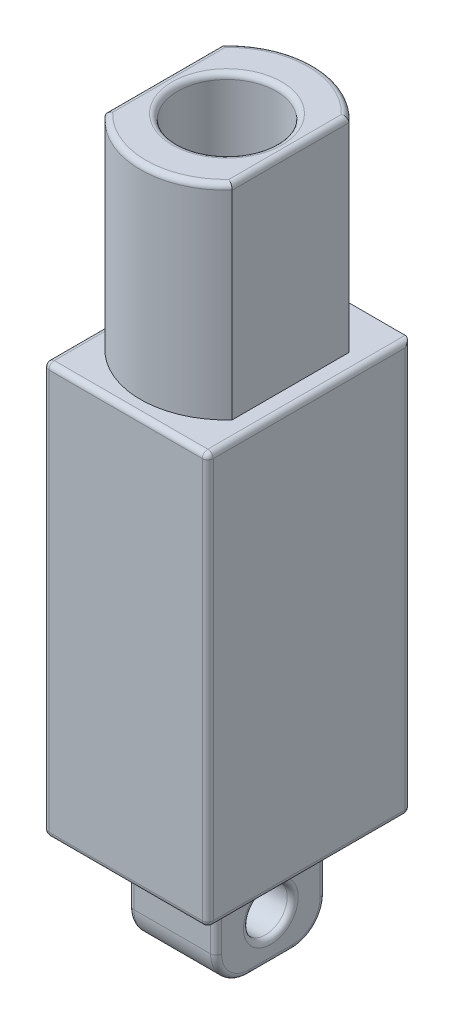
SolidWorks part; units mm, degrees
ref_plane "Front Plane" through (0, 0, 0) normal (0, 0, 1) x (1, 0, 0)
ref_plane "Top Plane" through (0, 0, 0) normal (0, 1, 0) x (1, 0, 0)
ref_plane "Right Plane" through (0, 0, 0) normal (1, 0, 0) x (0, 0, -1)
sketch "Sketch1" plane through (0, 0, 0) normal (0, 1, 0) x (1, 0, 0)
  line L1 (-7.5, -9.25) -> (7.5, -9.25)
  line L2 (-7.5, -9.25) -> (-7.5, 9.25)
  line L3 (-7.5, 9.25) -> (7.5, 9.25)
  line L4 (7.5, -9.25) -> (7.5, 9.25)
  line L5 (-7.5, -9.25) -> (7.5, 9.25) construction
  line L6 (-7.5, 9.25) -> (7.5, -9.25) construction
  point P0 (0, 0)
  dimension "D1" = 18.5
  dimension "D2" = 15
extrude "Boss-Extrude1" add sketch "Sketch1" along normal blind 37.5
sketch "Sketch2" plane through (0, 0, 0) normal (0, -1, 0) x (1, 0, 0)
  line L1 (-4, -4.9986) -> (4, -4.9986)
  line L2 (-4, -4.9986) -> (-4, 4.9986)
  line L3 (-4, 4.9986) -> (4, 4.9986)
  line L4 (4, -4.9986) -> (4, 4.9986)
  line L5 (-4, -4.9986) -> (4, 4.9986) construction
  line L6 (-4, 4.9986) -> (4, -4.9986) construction
  point P0 (0, 0)
  dimension "D1" = 9.9972
  dimension "D2" = 8
extrude "Boss-Extrude2" add sketch "Sketch2" along normal blind 9
sketch "Sketch3" plane through (0, 37.5, 0) normal (0, 1, 0) x (1, 0, 0)
  line L1 (-5.8, -7.9) -> (5.8, -7.9)
  line L2 (-5.8, -7.9) -> (-5.8, 7.9)
  line L3 (-5.8, 7.9) -> (5.8, 7.9)
  line L4 (5.8, -7.9) -> (5.8, 7.9)
  line L5 (-5.8, -7.9) -> (5.8, 7.9) construction
  line L6 (-5.8, 7.9) -> (5.8, -7.9) construction
  line L7 (5.8, -5.325) -> (-5.8, -5.325)
  line L8 (5.8, -5.325) -> (5.8, 5.325)
  line L9 (5.8, 5.325) -> (-5.8, 5.325)
  line L10 (-5.8, -5.325) -> (-5.8, 5.325)
  line L11 (5.8, -5.325) -> (-5.8, 5.325) construction
  line L12 (5.8, 5.325) -> (-5.8, -5.325) construction
  arc A0 (-5.8, 5.325) -> (5.8, 5.325) centre (0, 0.0805) cw
  arc A1 (-5.8, -5.325) -> (5.8, -5.325) centre (0, -0.0805) ccw
  point P0 (0, 0)
  point P6 (0, 0)
  dimension "D1" = 15.8
  dimension "D2" = 11.6
  dimension "D3" = 10.65
extrude "Boss-Extrude3" add sketch "Sketch3" along normal blind 18.65 contours A0 L9 | L4 L9 L2 L7 | A1 L7
sketch "Sketch4" plane through (0, 56.15, 0) normal (0, 1, 0) x (1, 0, 0)
  circle A0 centre (0, 0) radius 4.5
  dimension "D1" = 9
extrude "Cut-Extrude1" cut sketch "Sketch4" against normal blind 20.32
sketch "Sketch5" plane through (-4, 0, 0) normal (-1, 0, 0) x (0, 0, 1)
  line L0 (4.9986, -9) -> (-4.9986, -9) construction
  circle A0 centre (0, -5) radius 2
  dimension "D2" = 4
  dimension "D1" = 4
extrude "Cut-Extrude2" cut sketch "Sketch5" against normal up to next
fillet "Fillet1" radius 3 2 edges at (0, -9, -4.9986) (0, -9, 4.9986)
fillet "Fillet2" radius 0.5 27 edges at (4, -8.1213, 4.1199) (4, -3, 4.9986) (4, -3, -4.9986) (4, -8.1213, -4.1199) (4, -9, 0) (4, -5, 2) (-4, -3, 4.9986) (-4, -8.1213, 4.1199) (-4, -9, 0) (-4, -8.1213, -4.1199) (-4, -3, -4.9986) (-4, -5, 2) (0, 0, -9.25) (0, 0, 4.9986) (-4, 0, 0) (0, 0, -4.9986) (4, 0, 0) (-7.5, 18.75, -9.25) (-7.5, 37.5, 0) (-7.5, 0, 0) (7.5, 37.5, 0) (7.5, 18.75, -9.25) (7.5, 0, 0) (-7.5, 18.75, 9.25) (0, 37.5, 9.25) (7.5, 18.75, 9.25) (0, 0, 9.25)
fillet "Fillet3" radius 0.5 5 edges at (5.8, 56.15, 0) (0, 56.15, 7.9) (-5.8, 56.15, 0) (0, 56.15, -7.9) (0, 56.15, 4.5)
